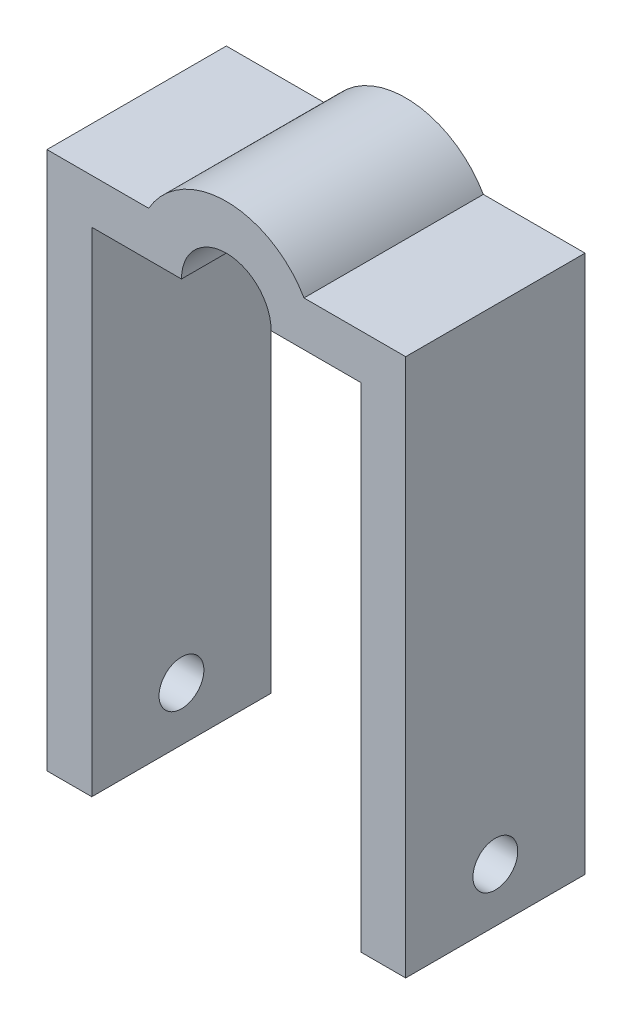
SolidWorks part; units mm, degrees
ref_plane "Front Plane" through (0, 0, 0) normal (0, 0, 1) x (1, 0, 0)
ref_plane "Top Plane" through (0, 0, 0) normal (0, 1, 0) x (1, 0, 0)
ref_plane "Right Plane" through (0, 0, 0) normal (1, 0, 0) x (0, 0, -1)
sketch "Sketch1" plane through (0, 0, 0) normal (0, 0, 1) x (1, 0, 0)
  line L0 (0, 0) -> (0, 34.925)
  line L1 (0, 34.925) -> (6.35, 34.925)
  line L2 (12.7, 34.925) -> (19.05, 34.925)
  line L3 (19.05, 34.925) -> (19.05, 0)
  line L5 (19.05, 0) -> (22.225, 0)
  line L6 (22.225, 0) -> (22.225, 38.1)
  line L7 (22.225, 38.1) -> (15.0243, 38.1)
  line L8 (0, 0) -> (-3.175, 0)
  line L9 (-3.175, 0) -> (-3.175, 38.1)
  line L10 (-3.175, 38.1) -> (4.0257, 38.1)
  arc A0 (12.7, 34.925) -> (6.35, 34.925) centre (9.525, 34.925) ccw
  arc A1 (15.0243, 38.1) -> (4.0257, 38.1) centre (9.525, 34.925) ccw
  dimension "D2" = 3.175
  dimension "D8" = 3.175
  dimension "D1" = 19.05
  dimension "D3" = 3.175
  dimension "D4" = 3.175
  dimension "D5" = 38.1
  dimension "D6" = 38.1
  dimension "D7" = 3.175
  dimension "D9" = 12.7
  dimension "D10" = 12.7
extrude "Boss-Extrude1" add sketch "Sketch1" along normal blind 12.7 contours L10 A1 L7 L6 L5 L3 L2 A0 L1 L0 L8 L9
sketch "Sketch2" plane through (-3.175, 0, 0) normal (-1, 0, 0) x (0, 0, 1)
  line L0 (0, 0) -> (0, 38.1) construction
  line L1 (12.7, 0) -> (0, 0) construction
  circle A0 centre (6.35, 3.81) radius 1.5875
  dimension "D1" = 3.175
  dimension "D2" = 6.35
  dimension "D3" = 3.81
extrude "Cut-Extrude1" cut sketch "Sketch2" against normal blind 76.2 contours A0
